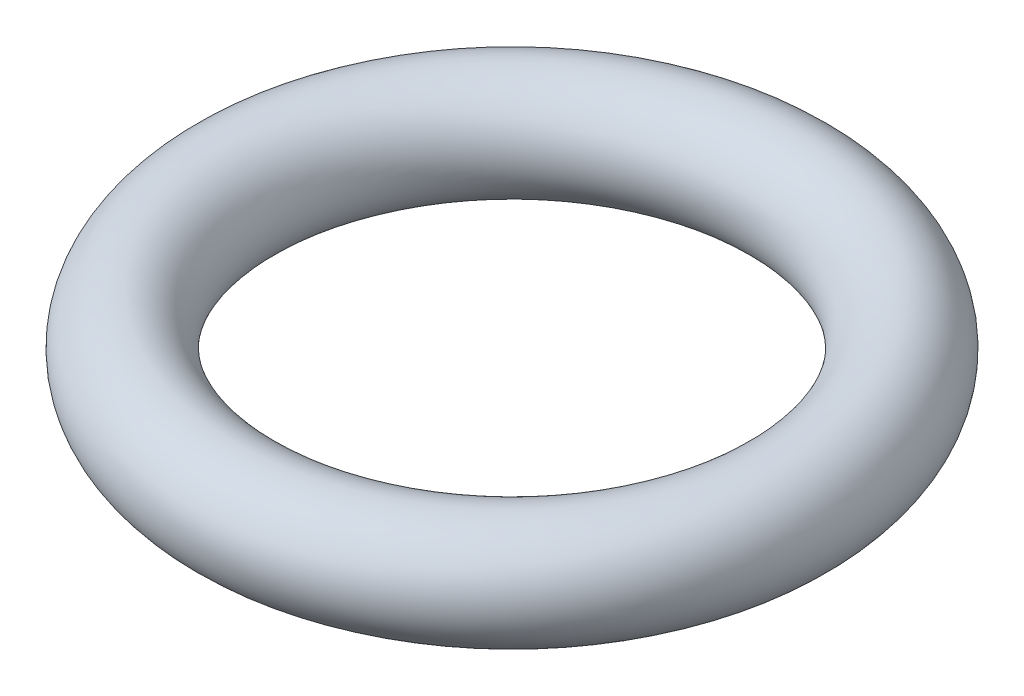
SolidWorks part; units mm, degrees
ref_plane "CL Y" through (0, 0, 0) normal (0, 0, 1) x (1, 0, 0)
ref_plane "Bottom" through (0, 0, 0) normal (0, 1, 0) x (1, 0, 0)
ref_plane "CL X" through (0, 0, 0) normal (1, 0, 0) x (0, 0, -1)
sketch "Sketch1" plane through (0, 0, 0) normal (0, 0, 1) x (1, 0, 0)
  line L0 (50, 0) -> (-50, 0) construction
  line L1 (0, -50) -> (0, 50) construction
  line L2 (0, 7.7946) -> (0, -11.854) construction
  circle A0 centre (-6.7, 0) radius 1.31
  dimension "D1" = 2.62
  dimension "D2" = 6.7
revolve "Revolve1" add sketch "Sketch1" angle 360 about L2
